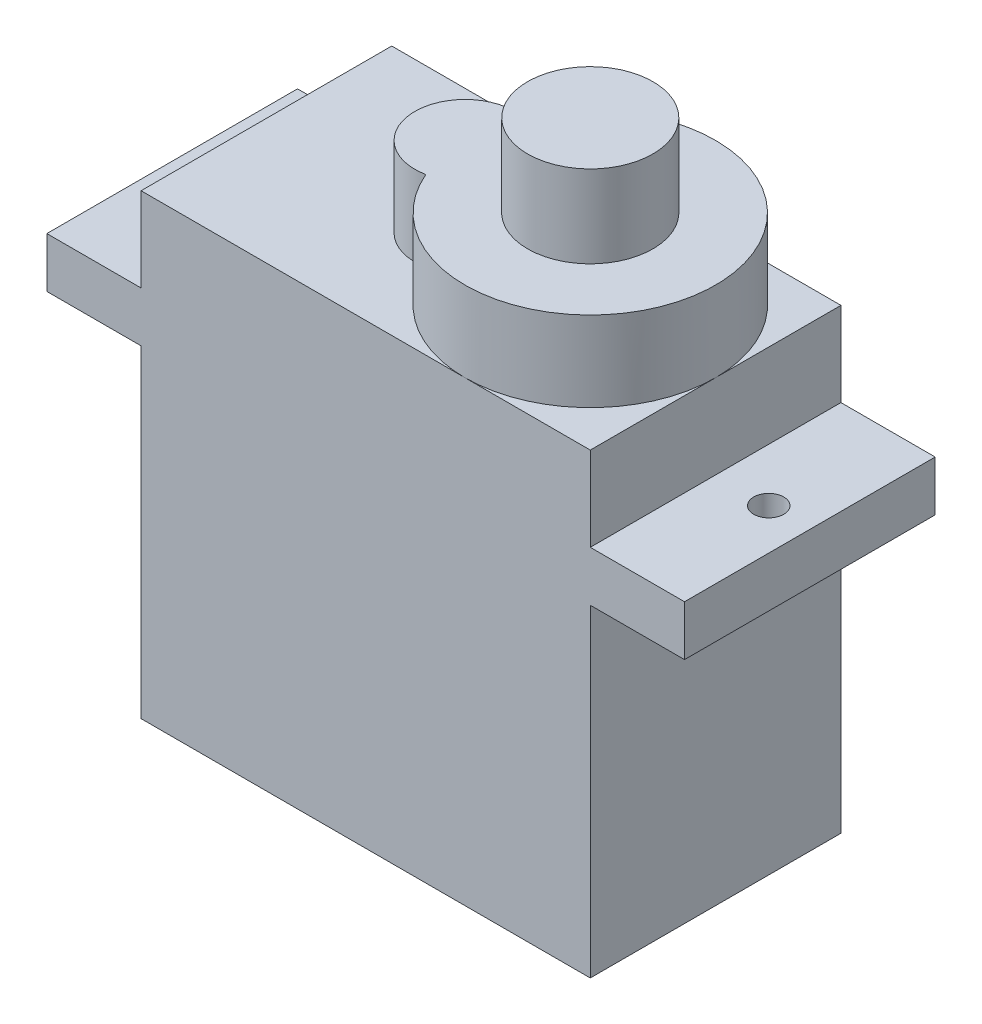
SolidWorks part; units mm, degrees
ref_plane "前视基准面" through (0, 0, 0) normal (0, 0, 1) x (1, 0, 0)
ref_plane "上视基准面" through (0, 0, 0) normal (0, 1, 0) x (1, 0, 0)
ref_plane "右视基准面" through (0, 0, 0) normal (1, 0, 0) x (0, 0, -1)
sketch "草图1" plane through (0, 0, 0) normal (0, 1, 0) x (1, 0, 0)
  line L1 (-11.2, -6.25) -> (11.2, -6.25)
  line L2 (-11.2, -6.25) -> (-11.2, 6.25)
  line L3 (-11.2, 6.25) -> (11.2, 6.25)
  line L4 (11.2, -6.25) -> (11.2, 6.25)
  line L5 (-11.2, -6.25) -> (11.2, 6.25) construction
  line L6 (-11.2, 6.25) -> (11.2, -6.25) construction
  point P0 (0, 0)
  dimension "D1" = 12.5
  dimension "D2" = 22.4
extrude "凸台-拉伸1" add sketch "草图1" along normal blind 22.8
sketch "草图2" plane through (0, 0, 0) normal (0, 1, 0) x (1, 0, 0)
  line L1 (-15.9, -6.25) -> (15.9, -6.25)
  line L2 (-15.9, -6.25) -> (-15.9, 6.25)
  line L3 (-15.9, 6.25) -> (15.9, 6.25)
  line L4 (15.9, -6.25) -> (15.9, 6.25)
  line L5 (-15.9, -6.25) -> (15.9, 6.25) construction
  line L6 (-15.9, 6.25) -> (15.9, -6.25) construction
  point P0 (0, 0)
  dimension "D1" = 12.5
  dimension "D2" = 31.8
extrude "凸台-拉伸2" add sketch "草图2" along normal blind 2.5 from offset 16.1
sketch "草图3" plane through (0, 18.6, 0) normal (0, 1, 0) x (1, 0, 0)
  line L0 (-1000, 0) -> (49000, 0) construction
  line L1 (0, -1000) -> (0, 49000) construction
  circle A0 centre (-13.85, 0) radius 0.75
  circle A1 centre (13.85, 0) radius 0.75
  dimension "D1" = 1.5
  dimension "D2" = 27.7
extrude "切除-拉伸1" cut sketch "草图3" against normal up to next
sketch "草图4" plane through (0, 22.8, 0) normal (0, 1, 0) x (1, 0, 0)
  line L0 (11.2, 6.25) -> (-11.2, 6.25) construction
  line L2 (11.2, 6.25) -> (11.2, -6.25) construction
  line L3 (-11.2, -6.25) -> (11.2, -6.25) construction
  line L4 (-1000, 0) -> (-3.8, 0) construction
  arc A0 (-0.8, -2.4495) -> (-0.8, 2.4495) centre (4.95, 0) ccw
  arc A1 (-0.8, 2.4495) -> (-0.8, -2.4495) centre (-1.3, 0) ccw
  dimension "D1" = 5
extrude "凸台-拉伸3" add sketch "草图4" along normal blind 4
sketch "草图6" plane through (0, 26.8, 0) normal (0, 1, 0) x (1, 0, 0)
  circle A0 centre (4.95, 0) radius 3.125
  dimension "D1" = 6.25
extrude "凸台-拉伸4" add sketch "草图6" along normal blind 4.1
